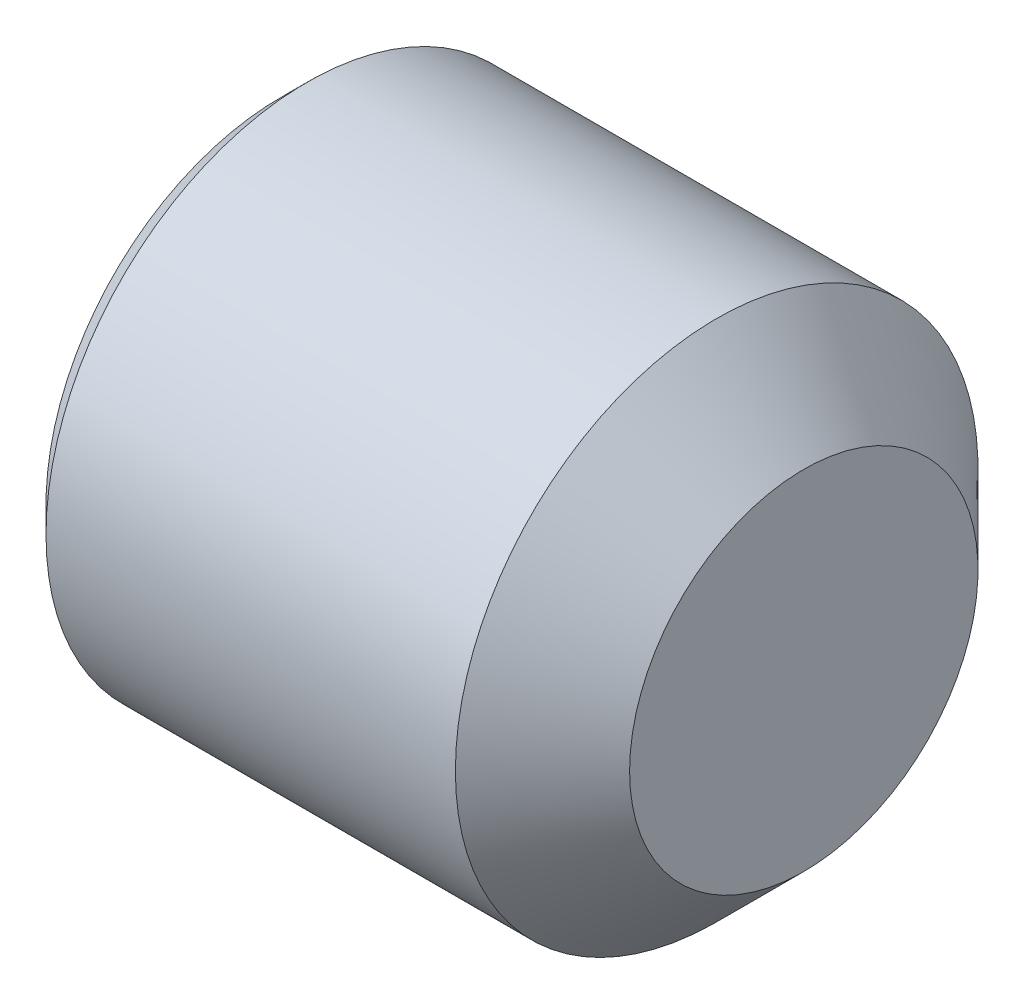
SolidWorks part; units mm, degrees
ref_plane "Front Plane" through (0, 0, 0) normal (0, 0, 1) x (1, 0, 0)
ref_plane "Top Plane" through (0, 0, 0) normal (0, 1, 0) x (1, 0, 0)
ref_plane "Right Plane" through (0, 0, 0) normal (1, 0, 0) x (0, 0, -1)
sketch "Sketch1" plane through (0, 0, 0) normal (0, 0, 1) x (1, 0, 0)
  line L0 (5, 3) -> (6, 2)
  line L1 (0, 0) -> (6, 0) construction
  line L2 (0, 0) -> (0, 3)
  line L3 (0, 3) -> (5, 3)
  line L4 (6, 0) -> (6, 2)
  line L5 (0, 0) -> (6, 0)
  dimension "MSM_1" = 6
  dimension "MSM_2" = 6
  dimension "FIX_11" = 45
  dimension "MSM_3" = 4
revolve "Revolve1" add sketch "Sketch1" angle 360 about L1
cosmetic thread "Thread3" parameters "ATD"=4.917
chamfer "Chamfer1" distance 0.3 1 edges at (0, 0, 3)
sketch "Sketch2" plane through (0, 0, 0) normal (1, 0, 0) x (0, 0, -1)
  line L0 (0, 1.5) -> (0, -1.5) construction
  line L1 (0, 1.7321) -> (-1.5, 0.866)
  line L2 (-1.5, 0.866) -> (-1.5, -0.866)
  line L3 (-1.5, -0.866) -> (0, -1.7321)
  line L4 (0, -1.7321) -> (1.5, -0.866)
  line L5 (1.5, -0.866) -> (1.5, 0.866)
  line L6 (1.5, 0.866) -> (0, 1.7321)
  line L7 (-1.5, 0) -> (1.5, 0) construction
  circle A0 centre (0, 0) radius 1.5 construction
  dimension "MSM_4" = 3
extrude "Cut-Extrude1" cut sketch "Sketch2" along normal blind 2
sketch "Sketch3" plane through (0, 0, 0) normal (0, 0, 1) x (1, 0, 0)
  line L0 (2, 0) -> (2.866, 0) construction
  line L1 (2, 0.866) -> (2, -0.866) construction
  line L2 (2.866, 0) -> (2, 1.5)
  line L3 (2, 1.7321) -> (2, 0.866) construction
  line L4 (2, 1.5) -> (2, 0)
  line L5 (2, 0) -> (2.866, 0)
  line L6 (0, 1.5) -> (2, 1.5) construction
  dimension "FIX_15" = 30
revolve "Cut-Revolve1" cut sketch "Sketch3" angle 360 about L0
